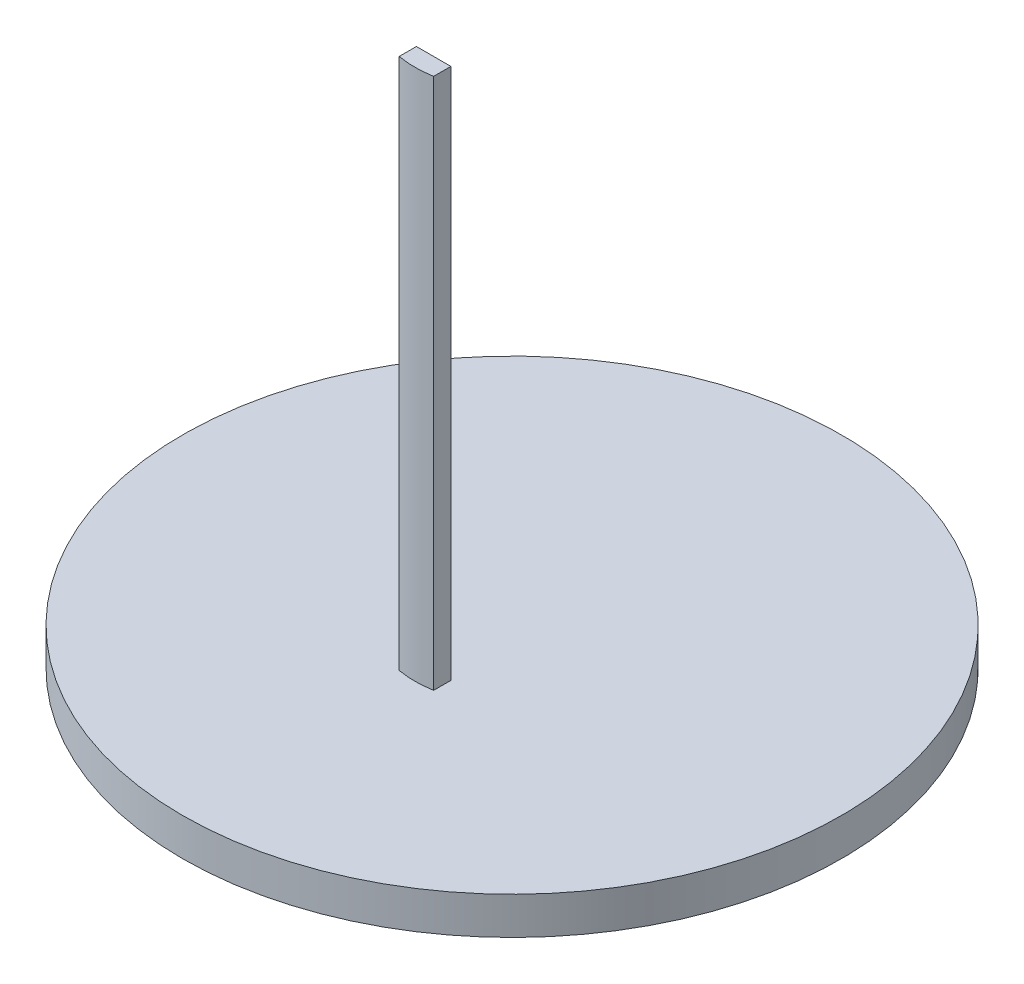
SolidWorks part; units mm, degrees
ref_plane "Front Plane" through (0, 0, 0) normal (0, 0, 1) x (1, 0, 0)
ref_plane "Top Plane" through (0, 0, 0) normal (0, 1, 0) x (1, 0, 0)
ref_plane "Right Plane" through (0, 0, 0) normal (1, 0, 0) x (0, 0, -1)
sketch "Sketch1" plane through (0, 0, 0) normal (0, 1, 0) x (1, 0, 0)
  circle A0 centre (0, 0) radius 88.01
  point P3 (0, 0)
extrude "Boss-Extrude1" add sketch "Sketch1" along normal blind 10
sketch "Sketch3" plane through (0, 10, 0) normal (0, 1, 0) x (1, 0, 0)
  line L2 (-4.6, -25.5492) -> (-4.6, -20.945)
  line L3 (-4.6, -20.945) -> (4.6, -20.945)
  line L4 (4.6, -25.5492) -> (4.6, -20.945)
  line L5 (0, -25.96) -> (4.6, -20.945) construction
  line L6 (-4.6, -20.945) -> (0, -25.96) construction
  circle A0 centre (0, 0) radius 25.96
  point P3 (0, -25.96)
  dimension "D1" = 51.92
  dimension "D2" = 9.2
extrude "Boss-Extrude5" add sketch "Sketch3" along normal blind 142 contours L2 A0 L4 L3
